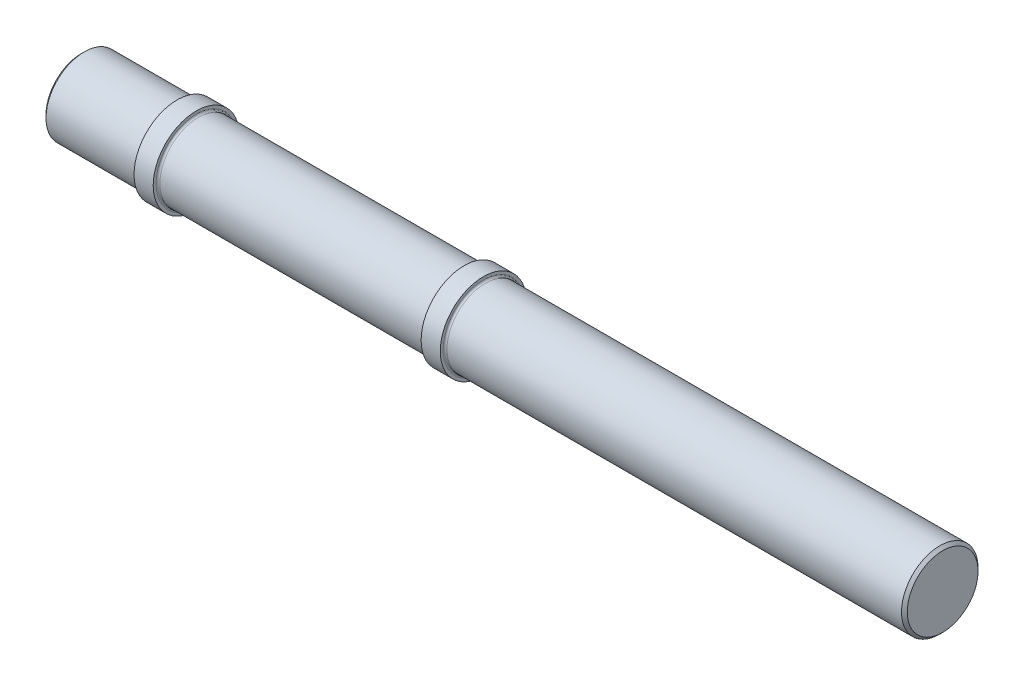
SolidWorks part; units mm, degrees
ref_plane "Front" through (0, 0, 0) normal (0, 0, 1) x (1, 0, 0)
ref_plane "Top" through (0, 0, 0) normal (0, 1, 0) x (1, 0, 0)
ref_plane "Right" through (0, 0, 0) normal (1, 0, 0) x (0, 0, -1)
sketch "Sketch1" plane through (0, 0, 0) normal (0, 0, 1) x (1, 0, 0)
  line L0 (0, 0) -> (90, 0) construction
  line L1 (10, 4) -> (10, 0)
  line L2 (0, 0) -> (90, 0)
  line L3 (0, 0) -> (0, 4)
  line L4 (0, 4) -> (10, 4)
  line L5 (90, 0) -> (90, 4)
  line L6 (12, 4) -> (12, 0)
  line L7 (20, 4) -> (20, 0)
  line L8 (32, 4) -> (32, 0)
  line L9 (40, 4) -> (40, 0)
  line L10 (42, 4) -> (42, 0)
  line L11 (52, 4) -> (52, 0)
  line L12 (10, 4) -> (10, 4.5)
  line L13 (10, 4.5) -> (12, 4.5)
  line L14 (12, 4.5) -> (12, 4)
  line L15 (12, 4) -> (40, 4)
  line L16 (40, 4) -> (40, 4.5)
  line L17 (40, 4.5) -> (42, 4.5)
  line L18 (42, 4.5) -> (42, 4)
  line L19 (42, 4) -> (90, 4)
  dimension "D1" = 90
  dimension "D2" = 8
  dimension "D3" = 10
  dimension "D4" = 12
  dimension "D5" = 20
  dimension "D6" = 32
  dimension "D7" = 40
  dimension "D8" = 42
  dimension "D9" = 52
  dimension "D10" = 0.5
  dimension "D11" = 0.5
revolve "Revolve1" add sketch "Sketch1" angle 360 about L0
fillet "Fillet1" radius 0.2 4 edges at (10, 0, 4) (12, 0, 4) (40, 0, 4) (42, 0, 4)
chamfer "Chamfer1" distance 0.3 angle 45 2 edges at (90, 0, 4) (0, 0, 4)
